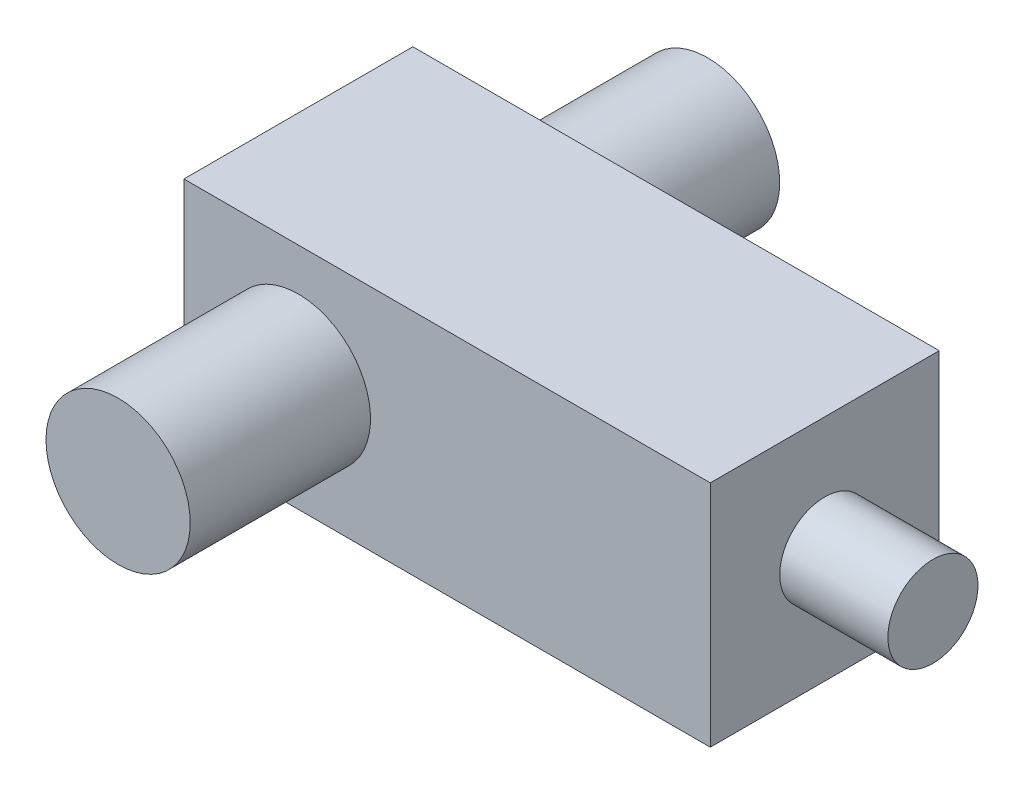
SolidWorks part; units mm, degrees
ref_plane "Front Plane" through (0, 0, 0) normal (0, 0, 1) x (1, 0, 0)
ref_plane "Top Plane" through (0, 0, 0) normal (0, 1, 0) x (1, 0, 0)
ref_plane "Right Plane" through (0, 0, 0) normal (1, 0, 0) x (0, 0, -1)
sketch "Sketch1" plane through (0, 0, 0) normal (0, 1, 0) x (1, 0, 0)
  line L1 (-14.6, -6.35) -> (14.6, -6.35)
  line L2 (-14.6, -6.35) -> (-14.6, 6.35)
  line L3 (-14.6, 6.35) -> (14.6, 6.35)
  line L4 (14.6, -6.35) -> (14.6, 6.35)
  line L5 (-14.6, -6.35) -> (14.6, 6.35) construction
  line L6 (-14.6, 6.35) -> (14.6, -6.35) construction
  point P0 (0, 0)
  dimension "D1" = 29.2
  dimension "D2" = 12.7
extrude "Boss-Extrude1" add sketch "Sketch1" along normal blind 12.7
sketch "Sketch2" plane through (0, 0, 6.35) normal (0, 0, 1) x (1, 0, 0)
  line L0 (-14.6, 6.35) -> (14.6, 6.35) construction
  line L1 (-14.6, 12.7) -> (-14.6, 0) construction
  line L2 (14.6, 12.7) -> (14.6, 0) construction
  circle A0 centre (-8.25, 6.35) radius 4
  dimension "D2" = 8
  dimension "D1" = 6.35
extrude "Boss-Extrude2" add sketch "Sketch2" along normal blind 10
mirror "Mirror1" about plane through (0, 0, 0) normal (0, 0, 1) of "Boss-Extrude2"
sketch "Sketch3" plane through (14.6, 0, 0) normal (1, 0, 0) x (0, 0, -1)
  line L0 (0, 0) -> (0, 12.7) construction
  line L1 (-6.35, 12.7) -> (6.35, 12.7) construction
  circle A0 centre (0, 6.35) radius 2.5
  dimension "D1" = 5
extrude "Boss-Extrude3" add sketch "Sketch3" along normal blind 6
